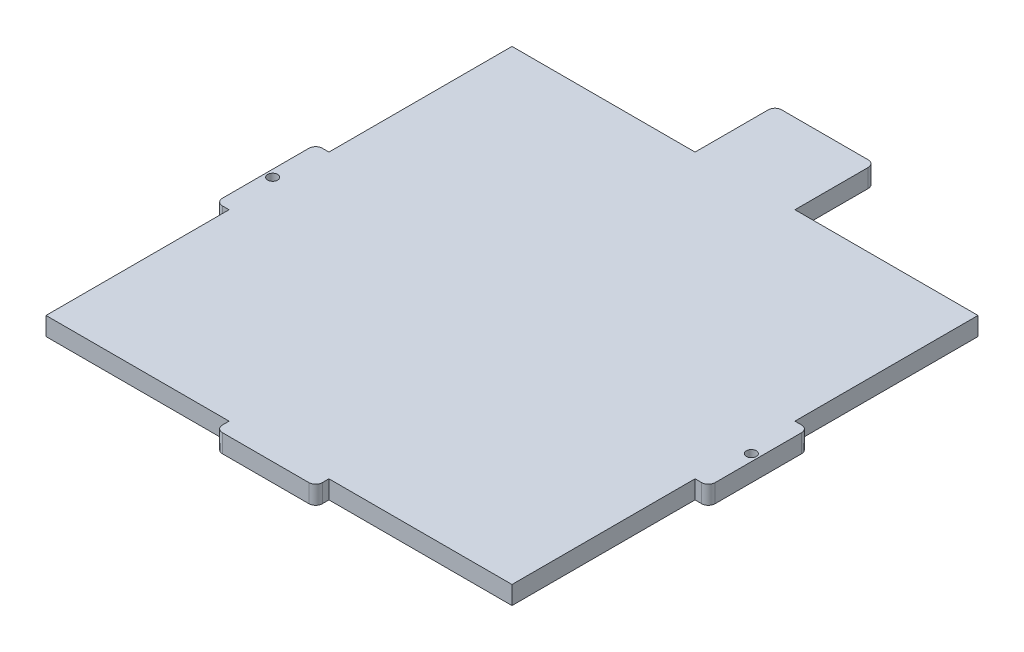
SolidWorks part; units mm, degrees
ref_plane "Front Plane" through (0, 0, 0) normal (0, 0, 1) x (1, 0, 0)
ref_plane "Top Plane" through (0, 0, 0) normal (0, 1, 0) x (1, 0, 0)
ref_plane "Right Plane" through (0, 0, 0) normal (1, 0, 0) x (0, 0, -1)
sketch "Sketch1" plane through (0, 0, 0) normal (0, 1, 0) x (1, 0, 0)
  line L0 (0, 85) -> (0, 140)
  line L1 (0, 0) -> (55, 0)
  line L2 (0, 0) -> (0, 55)
  line L3 (0, 140) -> (55, 140)
  line L4 (140, 0) -> (140, 55)
  line L6 (55, 0) -> (55, -4)
  line L7 (55, -4) -> (85, -4)
  line L8 (85, 0) -> (85, -4)
  line L9 (0, 85) -> (-4, 85)
  line L10 (85, 0) -> (140, 0)
  line L11 (0, 55) -> (-4, 55)
  line L12 (-4, 85) -> (-4, 55)
  line L14 (55, 140) -> (55, 164)
  line L15 (55, 164) -> (85, 164)
  line L16 (85, 140) -> (85, 164)
  line L17 (140, 85) -> (144, 85)
  line L19 (140, 55) -> (144, 55)
  line L20 (144, 85) -> (144, 55)
  line L21 (85, 140) -> (140, 140)
  line L22 (140, 85) -> (140, 140)
  circle A0 centre (-1.9, 70) radius 1.5
  circle A1 centre (141.9, 70) radius 1.5
  dimension "D15" = 3
  dimension "D18" = 3
  dimension "D1" = 140
  dimension "D2" = 140
  dimension "D3" = 30
  dimension "D4" = 55
  dimension "D5" = 4
  dimension "D6" = 4
  dimension "D7" = 24
  dimension "D8" = 4
  dimension "D9" = 30
  dimension "D10" = 55
  dimension "D11" = 55
  dimension "D12" = 30
  dimension "D13" = 30
  dimension "D14" = 55
  dimension "D16" = 15
  dimension "D17" = 2.1
  dimension "D19" = 2.1
  dimension "D20" = 15
extrude "Boss-Extrude1" add sketch "Sketch1" along normal blind 5.5
fillet "Fillet1" radius 2 8 edges at (55, 2.75, -164) (-4, 2.75, -85) (-4, 2.75, -55) (55, 2.75, 4) (85, 2.75, 4) (144, 2.75, -55) (144, 2.75, -85) (85, 2.75, -164)
